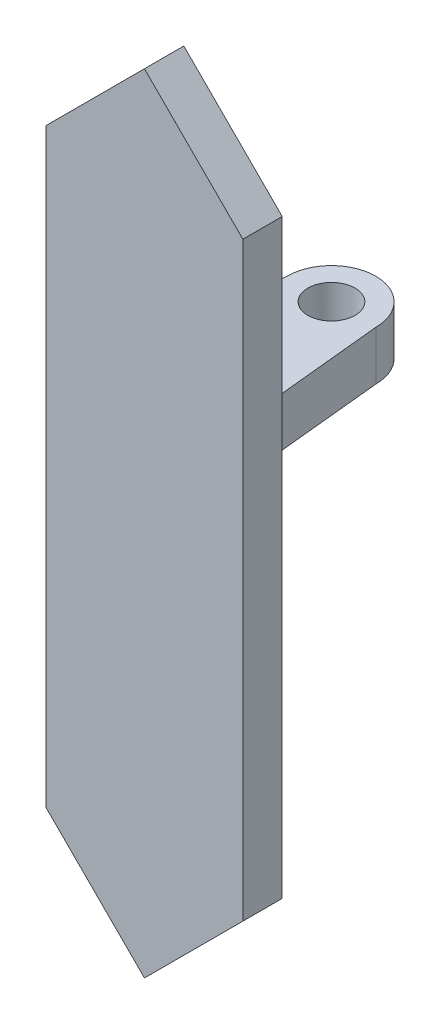
SolidWorks part; units mm, degrees
ref_plane "前视基准面" through (0, 0, 0) normal (0, 0, 1) x (1, 0, 0)
ref_plane "上视基准面" through (0, 0, 0) normal (0, 1, 0) x (1, 0, 0)
ref_plane "右视基准面" through (0, 0, 0) normal (1, 0, 0) x (0, 0, -1)
sketch "草图1" plane through (0, 0, 0) normal (0, 0, 1) x (1, 0, 0)
  line L2 (0.1473, 10) -> (0.1473, 70)
  line L4 (20.1473, 10) -> (20.1473, 70)
  line L5 (0.1473, 70) -> (10.1473, 80)
  line L6 (10.1473, 80) -> (20.1473, 70)
  line L8 (10.1473, 0) -> (20.1473, 10)
  line L9 (0.1473, 10) -> (10.1473, 0)
extrude "凸台-拉伸1" add sketch "草图1" along normal blind 4 contours L2 L9 L8 L4 L6 L5
sketch "草图2" plane through (0, 0, 0) normal (0, 0, -1) x (-1, 0, 0)
  line L0 (-10.1473, 50) -> (-10.1473, 80)
  line L5 (-16.1473, 50) -> (-4.1473, 50)
  line L6 (-16.1473, 50) -> (-16.1473, 45)
  line L7 (-16.1473, 45) -> (-4.1473, 45)
  line L8 (-4.1473, 50) -> (-4.1473, 45)
  line L9 (-16.1473, 50) -> (-4.1473, 45) construction
  line L10 (-16.1473, 45) -> (-4.1473, 50) construction
  point P8 (-10.1473, 47.5)
  dimension "D1" = 30
extrude "凸台-拉伸2" add sketch "草图2" along normal blind 20 contours L8 L5 L6 L7
sketch "草图6" plane through (0, 45, 0) normal (0, -1, 0) x (1, 0, 0)
  line L3 (5.6473, -15) -> (4.1473, 0)
  line L4 (14.6473, -15) -> (16.1473, 0)
  circle A0 centre (10.1473, -15) radius 4.5
  circle A1 centre (10.1473, -15) radius 2.4
  line M5 (4.1473, 0) -> (4.1473, -20)
  line M6 (4.1473, -20) -> (16.1473, -20)
  line M7 (16.1473, -20) -> (16.1473, 0)
extrude "切除-拉伸5" cut sketch "草图6" against normal blind 21 contours A1 | A0 L3 L4 M5 M6 M7
